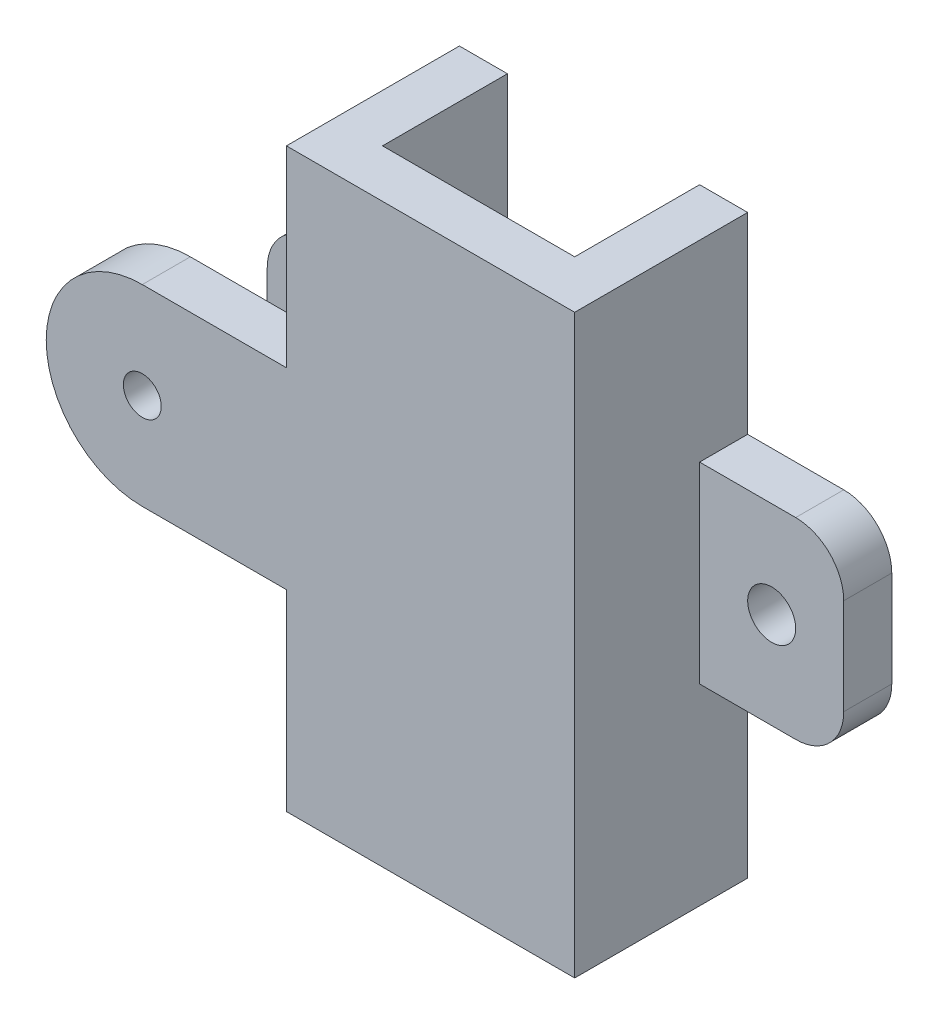
SolidWorks part; units mm, degrees
ref_plane "Front Plane" through (0, 0, 0) normal (0, 0, 1) x (1, 0, 0)
ref_plane "Top Plane" through (0, 0, 0) normal (0, 1, 0) x (1, 0, 0)
ref_plane "Right Plane" through (0, 0, 0) normal (1, 0, 0) x (0, 0, -1)
sketch "Sketch2" plane through (0, 0, 0) normal (0, 1, 0) x (1, 0, 0)
  line L1 (0, 0) -> (38.1, 0)
  line L2 (0, 0) -> (0, 22.86)
  line L3 (0, 22.86) -> (38.1, 22.86)
  line L4 (38.1, 0) -> (38.1, 22.86)
  line L5 (6.35, 22.86) -> (31.75, 22.86)
  line L6 (6.35, 22.86) -> (6.35, 6.35)
  line L7 (6.35, 6.35) -> (31.75, 6.35)
  line L8 (31.75, 22.86) -> (31.75, 6.35)
  dimension "D1" = 38.1
  dimension "D2" = 22.86
  dimension "D3" = 6.35
  dimension "D4" = 6.35
  dimension "D5" = 6.35
extrude "Boss-Extrude1" add sketch "Sketch2" along normal blind 76.2 contours L3 L8 L7 L6 L2 L1 L4
sketch "Sketch3" plane through (0, 0, 0) normal (0, 0, 1) x (1, 0, 0)
  line L1 (38.1, 76.2) -> (0, 76.2) construction
  line L2 (0, 76.2) -> (0, 0) construction
  line L3 (0, 0) -> (38.1, 0) construction
  line L4 (19.05, 50.8) -> (-19.05, 50.8)
  line L6 (-19.05, 25.4) -> (19.05, 25.4)
  arc A1 (19.05, 50.8) -> (19.05, 25.4) centre (19.05, 38.1) cw
  arc A2 (-19.05, 50.8) -> (-19.05, 25.4) centre (-19.05, 38.1) ccw
  circle A3 centre (-19.05, 38.1) radius 2.5019
  point P11 (19.05, 76.2)
  point P12 (19.05, 0)
  point P13 (0, 38.1)
  dimension "D1" = 12.7
  dimension "D3" = 5.0038
  dimension "D2" = 38.1
extrude "Boss-Extrude2" add sketch "Sketch3" against normal blind 6.35
sketch "Sketch4" plane through (0, 0, -22.86) normal (0, 0, -1) x (-1, 0, 0)
  line L0 (-38.1, 76.2) -> (-38.1, 0) construction
  line L1 (-38.1, 50.8) -> (-57.15, 50.8)
  line L2 (-38.1, 50.8) -> (-38.1, 25.4)
  line L3 (-38.1, 25.4) -> (-57.15, 25.4)
  line L4 (-57.15, 50.8) -> (-57.15, 25.4)
  line L5 (-57.15, 38.1) -> (-38.1, 38.1) construction
  line L6 (-47.625, 50.8) -> (-47.625, 25.4) construction
  line L7 (-38.1, 76.2) -> (0, 76.2) construction
  line L8 (-38.1, 0) -> (0, 0) construction
  line L9 (-19.05, 76.2) -> (-19.05, 0) construction
  line L10 (0, 25.4) -> (19.05, 25.4)
  line L11 (19.05, 50.8) -> (19.05, 25.4)
  line L12 (0, 50.8) -> (19.05, 50.8)
  line L13 (0, 50.8) -> (0, 25.4)
  circle A0 centre (-47.625, 38.1) radius 3.175
  circle A1 centre (9.525, 38.1) radius 3.175
  dimension "D4" = 6.35
  dimension "D1" = 25.4
  dimension "D2" = 25.4
  dimension "D3" = 19.05
extrude "Boss-Extrude3" add sketch "Sketch4" against normal blind 6.35
fillet "Fillet1" radius 6.35 4 edges at (57.15, 25.4, -19.685) (57.15, 50.8, -19.685) (-19.05, 25.4, -19.685) (-19.05, 50.8, -19.685)
